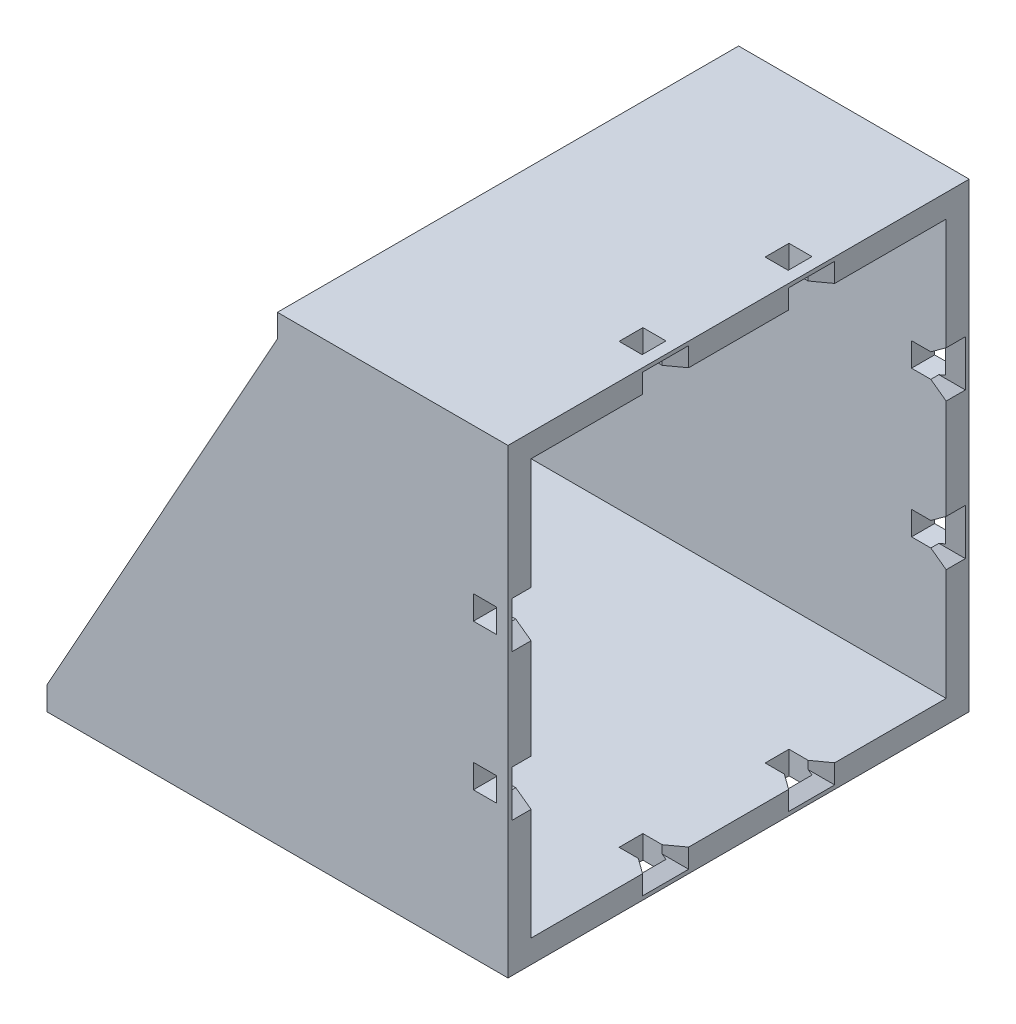
SolidWorks part; units mm, degrees
ref_plane "前视基准面" through (0, 0, 0) normal (0, 0, 1) x (1, 0, 0)
ref_plane "上视基准面" through (0, 0, 0) normal (0, 1, 0) x (1, 0, 0)
ref_plane "右视基准面" through (0, 0, 0) normal (1, 0, 0) x (0, 0, -1)
sketch "草图1" plane through (0, 0, 0) normal (0, 1, 0) x (1, 0, 0)
  line L1 (-30, 30) -> (30, 30)
  line L2 (-30, 30) -> (-30, -30)
  line L3 (-30, -30) -> (30, -30)
  line L4 (30, 30) -> (30, -30)
  line L5 (-30, 30) -> (30, -30) construction
  line L6 (-30, -30) -> (30, 30) construction
  point P0 (0, 0)
  dimension "D1" = 60
  dimension "D2" = 60
extrude "凸台-拉伸1" add sketch "草图1" along normal blind 3
ref_plane "基准面1" through (0, 57, 0) normal (0, 1, 0) x (1, 0, 0)
sketch "草图2" plane through (0, 57, 0) normal (0, 1, 0) x (1, 0, 0)
  line L1 (30, 30) -> (0, 30)
  line L2 (30, 30) -> (30, -30)
  line L3 (30, -30) -> (0, -30)
  line L4 (0, 30) -> (0, -30)
  dimension "D1" = 30
extrude "凸台-拉伸2" add sketch "草图2" along normal blind 3 separate body
sketch "草图3" plane through (0, 57, 0) normal (0, -1, 0) x (1, 0, 0)
  line L1 (0, 30) -> (3, 30)
  line L2 (0, 30) -> (0, -30)
  line L3 (0, -30) -> (3, -30)
  line L4 (3, 30) -> (3, -30)
  dimension "D1" = 3
sketch "草图4" plane through (0, 3, 0) normal (0, 1, 0) x (1, 0, 0)
  line L1 (-30, 30) -> (-27, 30)
  line L2 (-30, 30) -> (-30, -30)
  line L3 (-30, -30) -> (-27, -30)
  line L4 (-27, 30) -> (-27, -30)
  dimension "D1" = 3
loft "放样1" add profiles "草图3", "草图4"
sketch "草图5" plane through (0, 0, 30) normal (0, 0, 1) x (1, 0, 0)
  line L0 (30, 57) -> (3, 57)
  line L1 (3, 57) -> (-27, 3)
  line L2 (-27, 3) -> (30, 3)
  line L3 (30, 3) -> (30, 57)
extrude "凸台-拉伸3" add sketch "草图5" against normal blind 3
sketch "草图6" plane through (0, 0, -30) normal (0, 0, -1) x (-1, 0, 0)
  line L0 (-30, 57) -> (-3, 57)
  line L1 (-3, 57) -> (27, 3)
  line L3 (27, 3) -> (-30, 3)
  line L4 (-30, 3) -> (-30, 57)
extrude "凸台-拉伸4" add sketch "草图6" against normal blind 3
sketch "草图8" plane through (0, 0, -30) normal (0, 0, -1) x (-1, 0, 0)
  line L0 (-30, 60) -> (-30, 0) construction
  line L1 (-25.5, 41.05) -> (-28.5, 41.05)
  line L2 (-25.5, 41.05) -> (-25.5, 37.95)
  line L3 (-25.5, 37.95) -> (-28.5, 37.95)
  line L4 (-28.5, 41.05) -> (-28.5, 37.95)
  line L5 (-20.5533, 30) -> (-44.09, 30) construction
  line L6 (-30, 60) -> (0, 60) construction
  line L8 (-30, 57) -> (-30, 3) construction
  line L9 (-28.5, 18.95) -> (-28.5, 22.05)
  line L10 (-25.5, 22.05) -> (-28.5, 22.05)
  line L11 (-25.5, 18.95) -> (-25.5, 22.05)
  line L12 (-25.5, 18.95) -> (-28.5, 18.95)
  point P12 (-30, 30)
  dimension "D1" = 3.1
  dimension "D2" = 3
  dimension "D3" = 1.5
  dimension "D4" = 18.95
extrude "切除-拉伸2" cut sketch "草图8" against normal through all
sketch "草图9" plane through (0, 60, 0) normal (0, 1, 0) x (1, 0, 0)
  line L0 (16.0038, 0) -> (-8.6632, 0) construction
  line L1 (30, -30) -> (30, 30) construction
  line L2 (28.5, 11.05) -> (25.5, 11.05)
  line L3 (28.5, 11.05) -> (28.5, 7.95)
  line L4 (28.5, 7.95) -> (25.5, 7.95)
  line L5 (25.5, 11.05) -> (25.5, 7.95)
  line L6 (25.5, -11.05) -> (25.5, -7.95)
  line L7 (28.5, -7.95) -> (25.5, -7.95)
  line L8 (28.5, -11.05) -> (28.5, -7.95)
  line L9 (28.5, -11.05) -> (25.5, -11.05)
  line L10 (30, 30) -> (0, 30) construction
  dimension "D1" = 3.1
  dimension "D2" = 3
  dimension "D3" = 1.5
  dimension "D4" = 18.95
extrude "切除-拉伸3" cut sketch "草图9" against normal through all
sketch "草图7" plane through (30, 0, 0) normal (1, 0, 0) x (0, 0, -1)
  line L0 (6.5, 5.5) -> (6.5, 0.5)
  line L1 (16.8794, 30) -> (-18.0231, 30) construction
  line L2 (24.5, 36.5) -> (29.5, 36.5)
  line L3 (24.5, 36.5) -> (24.5, 42.5)
  line L4 (24.5, 42.5) -> (29.5, 42.5)
  line L5 (29.5, 36.5) -> (29.5, 42.5)
  line L6 (27, 57) -> (27, 3) construction
  line L7 (-30, 60) -> (30, 60) construction
  line L8 (29.5, 23.5) -> (29.5, 17.5)
  line L9 (24.5, 17.5) -> (29.5, 17.5)
  line L10 (24.5, 23.5) -> (24.5, 17.5)
  line L11 (24.5, 23.5) -> (29.5, 23.5)
  line L12 (6.5, 5.5) -> (12.5, 5.5)
  line L13 (12.5, 5.5) -> (12.5, 0.5)
  line L14 (6.5, 0.5) -> (12.5, 0.5)
  line L15 (-6.5, 0.5) -> (-12.5, 0.5)
  line L16 (-12.5, 5.5) -> (-12.5, 0.5)
  line L17 (-6.5, 5.5) -> (-12.5, 5.5)
  line L18 (-6.5, 5.5) -> (-6.5, 0.5)
  line L19 (-24.5, 23.5) -> (-29.5, 23.5)
  line L20 (-24.5, 23.5) -> (-24.5, 17.5)
  line L21 (-24.5, 17.5) -> (-29.5, 17.5)
  line L22 (-29.5, 23.5) -> (-29.5, 17.5)
  line L23 (-29.5, 36.5) -> (-29.5, 42.5)
  line L24 (-24.5, 42.5) -> (-29.5, 42.5)
  line L25 (-24.5, 36.5) -> (-24.5, 42.5)
  line L26 (-24.5, 36.5) -> (-29.5, 36.5)
  line L27 (-6.5, 54.5) -> (-6.5, 59.5)
  line L28 (-6.5, 54.5) -> (-12.5, 54.5)
  line L29 (-12.5, 54.5) -> (-12.5, 59.5)
  line L30 (-6.5, 59.5) -> (-12.5, 59.5)
  line L31 (6.5, 59.5) -> (12.5, 59.5)
  line L32 (12.5, 54.5) -> (12.5, 59.5)
  line L33 (6.5, 54.5) -> (12.5, 54.5)
  line L34 (6.5, 54.5) -> (6.5, 59.5)
  line L35 (-27, 3) -> (27, 57) construction
  point P6 (-0.5718, 30)
  point P9 (27, 30)
  point P10 (27, 42.5)
  point P19 (0, 0)
  point P44 (0, 30)
  point P46 (-1.9161, 13.7736)
  point P47 (0, 0)
  point P48 (0, 30)
  point P49 (0, 0)
  dimension "D1" = 5
  dimension "D2" = 6
  dimension "D3" = 17.5
extrude "切除-拉伸1" cut sketch "草图7" against normal blind 2 draft 36
